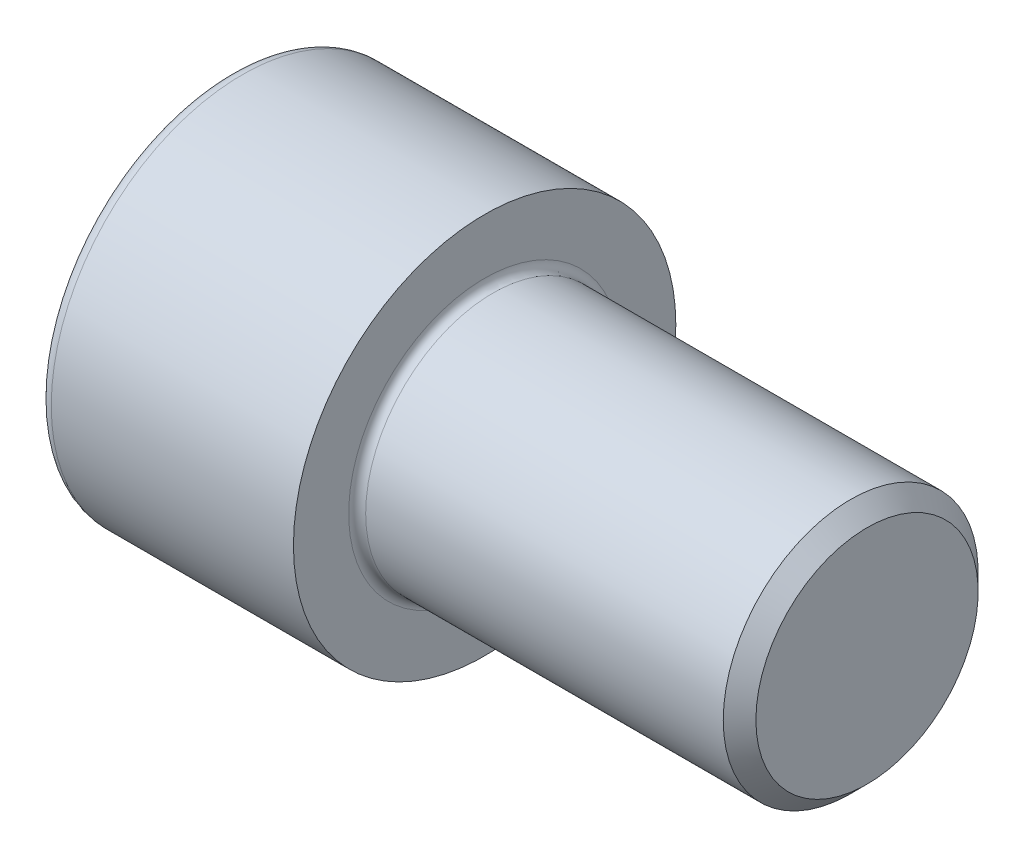
SolidWorks part; units mm, degrees
revolve "Base-Revolve" add sketch "BodySke"
sketch "BodySke" plane through (0, 0, 0) normal (0, 0, 1) x (1, 0, 0)
  line L0 (0, 0) -> (0, 22.5)
  line L1 (0, 22.5) -> (30, 22.5)
  line L2 (30, 22.5) -> (30, 15)
  line L3 (30, 15) -> (73.079, 15)
  line L4 (75, 13.079) -> (75, 0)
  line L5 (75, 0) -> (0, 0)
  line L6 (-31.75, 0) -> (127, 0) construction
  line L8 (75, 13.079) -> (73.079, 15)
  line L10 (75, -13.079) -> (73.079, -15) construction
  line L11 (33.5, 9.525) -> (33.5, 3.175) construction
  line L12 (30, 9.525) -> (30, 3.175) construction
  line L13 (15, 9.525) -> (15, 3.175) construction
  dimension "Head_ht" = 30
  dimension "Length" = 45
  dimension "Body_ch_ang" = 45
  dimension "Diameter" = 30
  dimension "Minor_dia" = 26.158
  dimension "Advance" = 3.5
  dimension "Thread_nom" = 45
  dimension "Thread_length" = 60
  dimension "Head_dia" = 45
cosmetic thread "ThreadCosmetic" [suppressed]
fillet "Fillet1" radius 1 1 edges at (30, 0, 15)
fillet "Fillet2" radius 1.5 1 edges at (0, 0, 22.5)
ref_plane "Plane1" through (0, 0, 0) normal (0, 0, 1) x (1, 0, 0)
ref_plane "Plane2" through (0, 0, 0) normal (0, 1, 0) x (1, 0, 0)
ref_plane "Plane3" through (0, 0, 0) normal (1, 0, 0) x (0, 0, -1)
sketch "Sketch2" plane through (0, 0, 0) normal (0, 0, 1) x (1, 0, 0)
  line L0 (0, 11.1375) -> (15.5, 11.1375)
  line L1 (15.5, 11.1375) -> (21.9302, 0)
  line L2 (-31.75, 0) -> (127, 0) construction
  line L3 (21.9302, 0) -> (0, 0)
  line L4 (0, 0) -> (0, 11.1375)
  line L6 (0, 0) -> (47.625, 0) construction
  dimension "D1" = 11.1375
  dimension "D2" = 60
  dimension "Depth" = 15.5
revolve "Hex-PreBroach" cut sketch "Sketch2" angle 360 about L6
sketch "Sketch3" plane through (0, 0, 0) normal (-1, 0, 0) x (0, 0.5, 0.866)
  line L0 (6.4302, 11.1375) -> (-6.4302, 11.1375)
  line L1 (-6.4302, 11.1375) -> (-12.8605, 0)
  line L2 (6.4302, 11.1375) -> (12.8605, 0)
  line L3 (6.4302, -11.1375) -> (12.8605, 0)
  line L4 (6.4302, -11.1375) -> (-6.4302, -11.1375)
  line L5 (-6.4302, -11.1375) -> (-12.8605, 0)
  dimension "D1" = 11.1375
  dimension "D2" = 11.1375
  dimension "Hex_size" = 22.275
extrude "Hex" cut sketch "Sketch3" against normal blind 15.5
sketch "ThdSchSke" plane through (0, 0, 0) normal (0, 0, 1) x (1, 0, 0)
  line L0 (40.5, -13.079) -> (39.1549, -15)
  line L1 (40.5, -13.079) -> (41.8451, -15)
  line L2 (41.8451, -15) -> (41.8451, -18.75)
  line L3 (-3.175, 0) -> (5.1513, 0) construction
  line L4 (0, 21) -> (0, -21) construction
  line L5 (41.8451, -18.75) -> (39.1549, -18.75)
  line L6 (39.1549, -18.75) -> (39.1549, -15)
  dimension "Thread_minor" = 26.158
  dimension "Diameter" = 30
  dimension "Start" = 40.5
revolve "ThreadSchematic" [suppressed] cut sketch "ThdSchSke" angle 360 about L3
pattern_linear "ThdSchPat" [suppressed]
equation "\"D2@Sketch3\" = \"Hex_size@Sketch3\" / 2"
equation "\"D1@Sketch3\" = \"Hex_size@Sketch3\" / 2"
equation "\"D1@Sketch2\" = \"Hex_size@Sketch3\" / 2"
equation "\"Thread_minor@ThreadCosmetic\"  =  \"Minor_dia@BodySke\""
equation "\"Depth@Sketch2\" =  \"Key_eng@Hex\""
equation "\"Thread_length@ThreadCosmetic\" = ((sgn( (\"Length@BodySke\" - \"Advance@BodySke\" * 3.0) - \"Thread_nom@BodySke\" )-1)*( (\"Length@BodySke\" - \"Advance@BodySke\" * 3.0) - \"Thread_nom@BodySke\" ))/-2+ \"Thread_nom@BodySke\""
equation "\"Thread_minor@ThdSchSke\" = \"Minor_dia@BodySke\""
equation "\"Diameter@ThdSchSke\" = \"Diameter@BodySke\""
equation "\"Overcut@ThdSchSke\" = \"Diameter@BodySke\" * 1.25"
equation "\"Start@ThdSchSke\" = \"Head_ht@BodySke\" + \"Length@BodySke\" - \"Thread_length@ThreadCosmetic\"  '---Non-countersunk---"
equation "\"Num_threads@ThdSchPat\" = int( \"Thread_length@ThreadCosmetic\" / \"Advance@BodySke\" + 0.999 )  + 1"
equation "\"Advance@ThdSchPat\" = \"Thread_length@ThreadCosmetic\" /  (\"Num_threads@ThdSchPat\" - 1) 'relax it"
equation "\"Num_threads@ThdSchPat\" = \"Num_threads@ThdSchPat\" - sgn( \"Num_threads@ThdSchPat\" - 1) '---chamfered tips only---"
